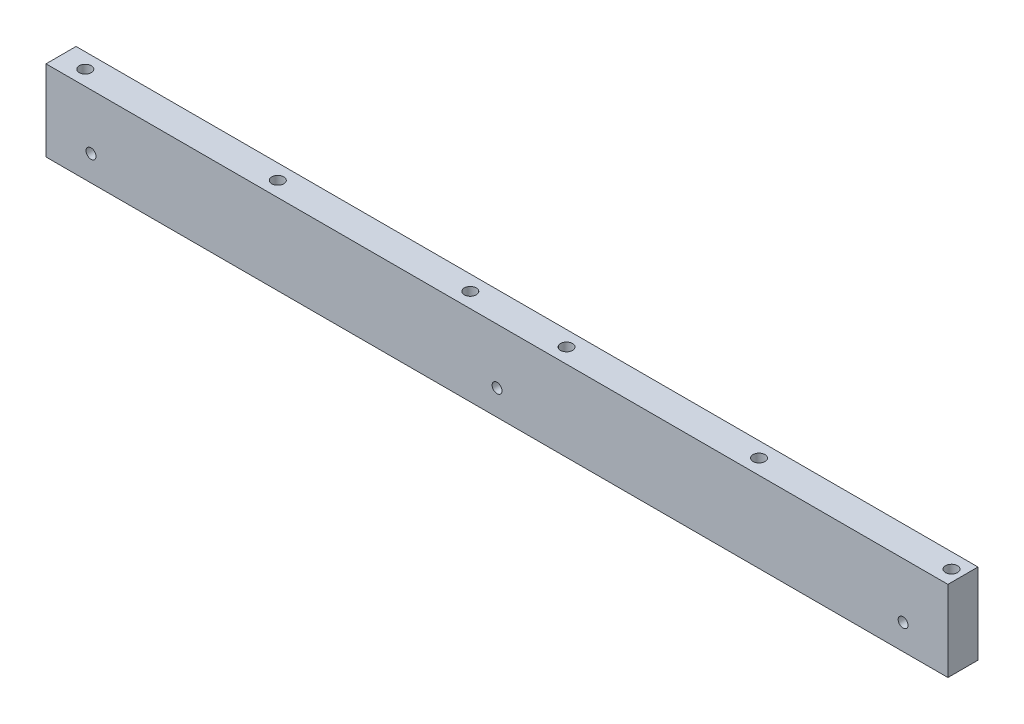
SolidWorks part; units mm, degrees
ref_plane "Front Plane" through (0, 0, 0) normal (0, 0, 1) x (1, 0, 0)
ref_plane "Top Plane" through (0, 0, 0) normal (0, 1, 0) x (1, 0, 0)
ref_plane "Right Plane" through (0, 0, 0) normal (1, 0, 0) x (0, 0, -1)
sketch "Sketch2" plane through (0, 0, 16) normal (0, 0, 1) x (1, 0, 0)
  line L0 (-14.9619, 18.3491) -> (-14.9575, -8.4878)
  line L1 (-14.9619, 18.3491) -> (284.9081, 18.3981)
  line L2 (-14.9575, -8.4878) -> (284.9125, -8.4389)
  line L3 (284.9081, 18.3981) -> (284.9125, -8.4389)
extrude "Boss-Extrude2" add sketch "Sketch2" along normal blind 10 contours L0 L1 L3 L2
sketch "Sketch6" plane through (0, 0, 16) normal (0, 0, -1) x (-1, 0, 0)
  circle A0 centre (-135.0026, -0.0059) radius 1.6368
extrude "Cut-Extrude1" cut sketch "Sketch6" against normal blind 27
sketch "Sketch7" plane through (0, 0, 16) normal (0, 0, -1) x (-1, 0, 0)
  circle A0 centre (-269.9988, -0.0074) radius 1.638
extrude "Cut-Extrude2" cut sketch "Sketch7" against normal blind 27
sketch "Sketch8" plane through (0, 0, 16) normal (0, 0, -1) x (-1, 0, 0)
  circle A0 centre (-0.0051, -0.0111) radius 1.6507
extrude "Cut-Extrude3" cut sketch "Sketch8" against normal blind 27
sketch "Sketch12" plane through (284.9111, 0.0465, 0) normal (1, 0.0002, 0) x (0, 0, -1)
sketch "Sketch14" plane through (-0.003, 18.3516, 0) normal (-0.0002, 1, 0) x (1, 0.0002, 0)
  line L0 (-14.9026, -15.9986) -> (-14.9723, -26.002) construction
  circle A0 centre (-6.8729, -21.0249) radius 2.0033
  circle A2 centre (57.1271, -21.0249) radius 2.0033
  circle A4 centre (121.1271, -21.0249) radius 2.0033
  circle A5 centre (153.1271, -21.0249) radius 2.0033
  circle A7 centre (217.1271, -21.0249) radius 2.0033
  circle A9 centre (281.1271, -21.0249) radius 2.0033
  circle A10 centre (25.1271, -21.0249) radius 2.0033 [skipped]
  circle A11 centre (89.1271, -21.0249) radius 2.0033 [skipped]
  circle A12 centre (185.1271, -21.0249) radius 2.0033 [skipped]
  circle A13 centre (249.1271, -21.0249) radius 2.0033 [skipped]
  dimension "D1" = 10
extrude "Cut-Extrude4" cut sketch "Sketch14" against normal blind 27
